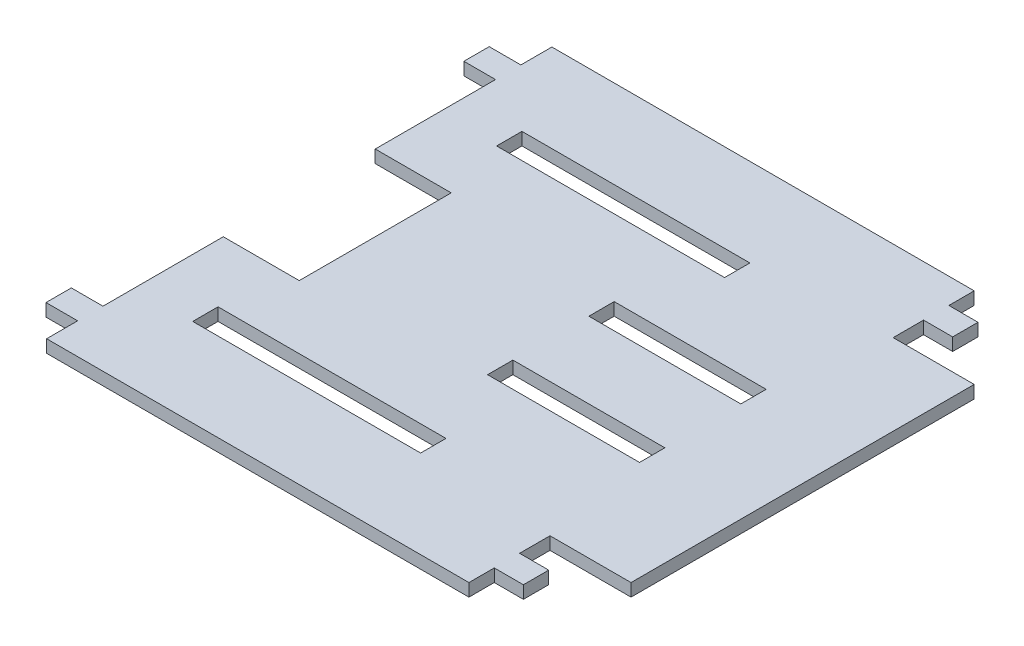
SolidWorks part; units mm, degrees
ref_plane "Alzado" through (0, 0, 0) normal (0, 0, 1) x (1, 0, 0)
ref_plane "Planta" through (0, 0, 0) normal (0, 1, 0) x (1, 0, 0)
ref_plane "Vista lateral" through (0, 0, 0) normal (1, 0, 0) x (0, 0, -1)
sketch "Croquis2" plane through (0, 0, 0) normal (0, 1, 0) x (1, 0, 0)
  line L0 (-81.5023, 77) -> (-92.5023, 77) construction
  line L1 (-92.5023, 77) -> (-92.5023, 88) construction
  line L2 (-92.5023, 88) -> (-81.5023, 88) construction
  line L3 (-81.5023, 97.5) -> (-81.5023, 88) construction
  line L4 (-129.5023, 97.5) -> (-81.5023, 97.5) construction
  line L5 (99.2488, 90.2512) -> (99.2488, 79.2512) construction
  line L6 (89.2488, 90.2512) -> (99.2488, 90.2512) construction
  line L7 (89.2488, 99.7512) -> (89.2488, 90.2512) construction
  line L8 (119.2488, 69.7512) -> (119.2488, 99.7512) construction
  line L9 (119.2488, 99.7512) -> (89.2488, 99.7512) construction
  line L10 (-81.5023, 77) -> (-92.5023, 77) construction
  line L11 (-92.5023, 77) -> (-92.5023, 88) construction
  line L12 (-92.5023, 88) -> (-81.5023, 88) construction
  line L13 (-81.5023, 97.5) -> (-81.5023, 88) construction
  line L14 (-129.5023, 97.5) -> (-81.5023, 97.5) construction
  line L15 (99.2488, 90.2512) -> (99.2488, 79.2512) construction
  line L16 (89.2488, 90.2512) -> (99.2488, 90.2512) construction
  line L17 (89.2488, 99.7512) -> (89.2488, 90.2512) construction
  line L18 (119.2488, 69.7512) -> (119.2488, 99.7512) construction
  line L19 (119.2488, 99.7512) -> (89.2488, 99.7512) construction
  line L20 (-222.2523, 0) -> (277.1189, 0) construction
  line L21 (89.2488, 69.7512) -> (99.2488, 69.7512) construction
  line L22 (89.2488, 79.2512) -> (89.2488, 69.7512) construction
  line L23 (99.2488, 79.2512) -> (89.2488, 79.2512) construction
  line L24 (-81.5023, 77) -> (-81.5023, 67.5) construction
  line L25 (89.2488, 69.7512) -> (99.2488, 69.7512) construction
  line L26 (89.2488, 79.2512) -> (89.2488, 69.7512) construction
  line L27 (99.2488, 79.2512) -> (89.2488, 79.2512) construction
  line L28 (-81.5023, 77) -> (-81.5023, 67.5) construction
  line L29 (119.2488, -67.7512) -> (119.2488, 67.7512)
  line L30 (119.2488, 67.7512) -> (87.2488, 67.7512)
  line L31 (87.2488, 67.7512) -> (87.2488, 79.7512)
  line L32 (87.2488, 79.7512) -> (98.7488, 79.7512)
  line L33 (98.7488, 79.7512) -> (98.7488, 89.7512)
  line L34 (98.7488, 89.7512) -> (87.2488, 89.7512)
  line L35 (87.2488, 89.7512) -> (87.2488, 99.7512)
  line L36 (87.2488, 99.7512) -> (-79.5023, 99.7512)
  line L37 (-79.5023, 99.7512) -> (-79.5023, 87.5)
  line L38 (-79.5023, 87.5) -> (-92.0023, 87.5)
  line L39 (-92.0023, 87.5) -> (-92.0023, 77.5)
  line L40 (-92.0023, 77.5) -> (-79.5023, 77.5)
  line L41 (-79.5023, 77.5) -> (-79.5023, 30)
  line L42 (-79.5023, 30) -> (-49.5023, 30)
  line L43 (-49.5023, 30) -> (-49.5023, -30)
  line L44 (-81.5023, -77) -> (-81.5023, -67.5) construction
  line L45 (99.2488, -79.2512) -> (89.2488, -79.2512) construction
  line L46 (89.2488, -79.2512) -> (89.2488, -69.7512) construction
  line L47 (89.2488, -69.7512) -> (99.2488, -69.7512) construction
  line L48 (119.2488, -99.7512) -> (89.2488, -99.7512) construction
  line L49 (119.2488, -69.7512) -> (119.2488, -99.7512) construction
  line L50 (89.2488, -99.7512) -> (89.2488, -90.2512) construction
  line L51 (89.2488, -90.2512) -> (99.2488, -90.2512) construction
  line L52 (99.2488, -90.2512) -> (99.2488, -79.2512) construction
  line L53 (-81.5023, -97.5) -> (-81.5023, -88) construction
  line L54 (-92.5023, -88) -> (-81.5023, -88) construction
  line L55 (-92.5023, -77) -> (-92.5023, -88) construction
  line L56 (-81.5023, -77) -> (-92.5023, -77) construction
  line L57 (-79.5023, -30) -> (-49.5023, -30)
  line L58 (-79.5023, -77.5) -> (-79.5023, -30)
  line L59 (-92.0023, -77.5) -> (-79.5023, -77.5)
  line L60 (-92.0023, -87.5) -> (-92.0023, -77.5)
  line L61 (-79.5023, -87.5) -> (-92.0023, -87.5)
  line L62 (-79.5023, -99.7512) -> (-79.5023, -87.5)
  line L63 (87.2488, -99.7512) -> (-79.5023, -99.7512)
  line L64 (87.2488, -89.7512) -> (87.2488, -99.7512)
  line L65 (98.7488, -89.7512) -> (87.2488, -89.7512)
  line L66 (98.7488, -79.7512) -> (98.7488, -89.7512)
  line L67 (87.2488, -79.7512) -> (98.7488, -79.7512)
  line L68 (87.2488, -67.7512) -> (87.2488, -79.7512)
  line L69 (119.2488, -67.7512) -> (87.2488, -67.7512)
  line L70 (-37.2209, -20) -> (102.5707, -20) construction
  line L71 (-66.264, -60) -> (60.5807, -60) construction
  line L72 (79.8516, 15) -> (19.8516, 15)
  line L73 (79.8516, -25) -> (19.8516, -25)
  line L74 (79.8516, -25) -> (79.8516, -15)
  line L75 (79.8516, -15) -> (19.8516, -15)
  line L76 (19.8516, -25) -> (19.8516, -15)
  line L77 (79.8516, -25) -> (19.8516, -15) construction
  line L78 (79.8516, -15) -> (19.8516, -25) construction
  line L79 (33.4265, -65) -> (-56.5735, -65)
  line L80 (33.4265, -65) -> (33.4265, -55)
  line L81 (33.4265, -55) -> (-56.5735, -55)
  line L82 (-56.5735, -65) -> (-56.5735, -55)
  line L83 (33.4265, -65) -> (-56.5735, -55) construction
  line L84 (33.4265, -55) -> (-56.5735, -65) construction
  line L85 (19.8516, 25) -> (19.8516, 15)
  line L86 (79.8516, 25) -> (19.8516, 25)
  line L87 (79.8516, 25) -> (79.8516, 15)
  line L88 (33.4265, 55) -> (-56.5735, 55)
  line L89 (-56.5735, 65) -> (-56.5735, 55)
  line L90 (33.4265, 65) -> (-56.5735, 65)
  line L91 (33.4265, 65) -> (33.4265, 55)
  point P52 (-49.5023, 0)
  point P65 (119.2488, 0)
  point P68 (49.8516, -20)
  point P73 (-11.5735, -60)
  point P86 (49.8516, -20)
  dimension "D16" = 60
  dimension "D1" = 2
  dimension "D2" = 2
  dimension "D3" = 0.5
  dimension "D4" = 1
  dimension "D5" = 0.5
  dimension "D6" = 2
  dimension "D7" = 2
  dimension "D8" = 0.5
  dimension "D9" = 1
  dimension "D10" = 0.5
  dimension "D11" = 2
  dimension "D12" = 30
  dimension "D13" = 30
  dimension "D14" = 20
  dimension "D15" = 60
  dimension "D17" = 10
  dimension "D18" = 90
  dimension "D19" = 10
extrude "Saliente-Extruir1" add sketch "Croquis2" along normal blind 5
